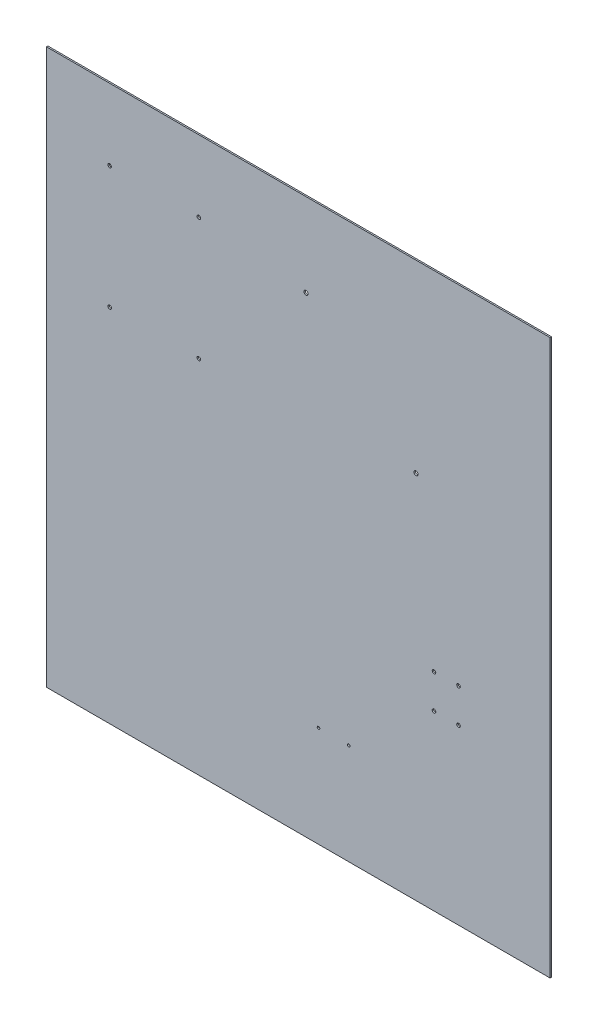
SolidWorks part; units mm, degrees
ref_plane "Plan de face" through (0, 0, 0) normal (0, 0, 1) x (1, 0, 0)
ref_plane "Plan de dessus" through (0, 0, 0) normal (0, 1, 0) x (1, 0, 0)
ref_plane "Plan de droite" through (0, 0, 0) normal (1, 0, 0) x (0, 0, -1)
sketch "Esquisse1" plane through (0, 0, 0) normal (0, 0, 1) x (1, 0, 0)
  line L1 (-62.5394, 35.2073) -> (360.4606, 35.2073)
  line L2 (-62.5394, 35.2073) -> (-62.5394, -430.7927)
  line L3 (-62.5394, -430.7927) -> (360.4606, -430.7927)
  line L4 (360.4606, 35.2073) -> (360.4606, -430.7927)
  dimension "D1" = 423
  dimension "D2" = 466
extrude "Boss.-Extru.1" add sketch "Esquisse1" along normal blind 1.2
sketch "Esquisse2" plane through (0, 0, 1.2) normal (0, 0, 1) x (1, 0, 0)
  line L0 (-62.5394, 35.2073) -> (-62.5394, -430.7927) construction
  line L1 (360.4606, 35.2073) -> (-62.5394, 35.2073) construction
  circle A0 centre (-9.5394, -24.7927) radius 1.5
  circle A1 centre (65.3906, -24.7927) radius 1.5
  circle A2 centre (65.3906, -127.6627) radius 1.5
  circle A3 centre (-9.5394, -127.6627) radius 1.5
  circle A4 centre (155.3906, -34.7927) radius 1.75
  circle A5 centre (247.8906, -119.7927) radius 1.75
  circle A10 centre (262.9748, -256.6973) radius 1.5
  circle A11 centre (262.9748, -285.2973) radius 1.5
  circle A12 centre (283.5748, -285.2973) radius 1.5
  circle A13 centre (283.5748, -256.6973) radius 1.5
  circle A14 centre (165.9543, -346.0821) radius 1.1
  circle A15 centre (191.3543, -346.0821) radius 1.1
  dimension "D1" = 3
  dimension "D2" = 53
  dimension "D5" = 85
  dimension "D6" = 92.5
  dimension "D7" = 3.5
  dimension "D8" = 3.5
  dimension "D9" = 90
  dimension "D10" = 70
  dimension "D11" = 60
  dimension "D20" = 28.6
  dimension "D21" = 20.6
  dimension "D22" = 3
  dimension "D23" = 3
  dimension "D24" = 3
  dimension "D25" = 3
  dimension "D27" = 28.6
  dimension "D28" = 25.4
  dimension "D29" = 2.2
  dimension "D30" = 2.2
  dimension "D26" = 20.6
  dimension "D3" = 2
  dimension "D4" = 2
extrude "Enlèv. mat.-Extru.1" cut sketch "Esquisse2" against normal blind 1.2
